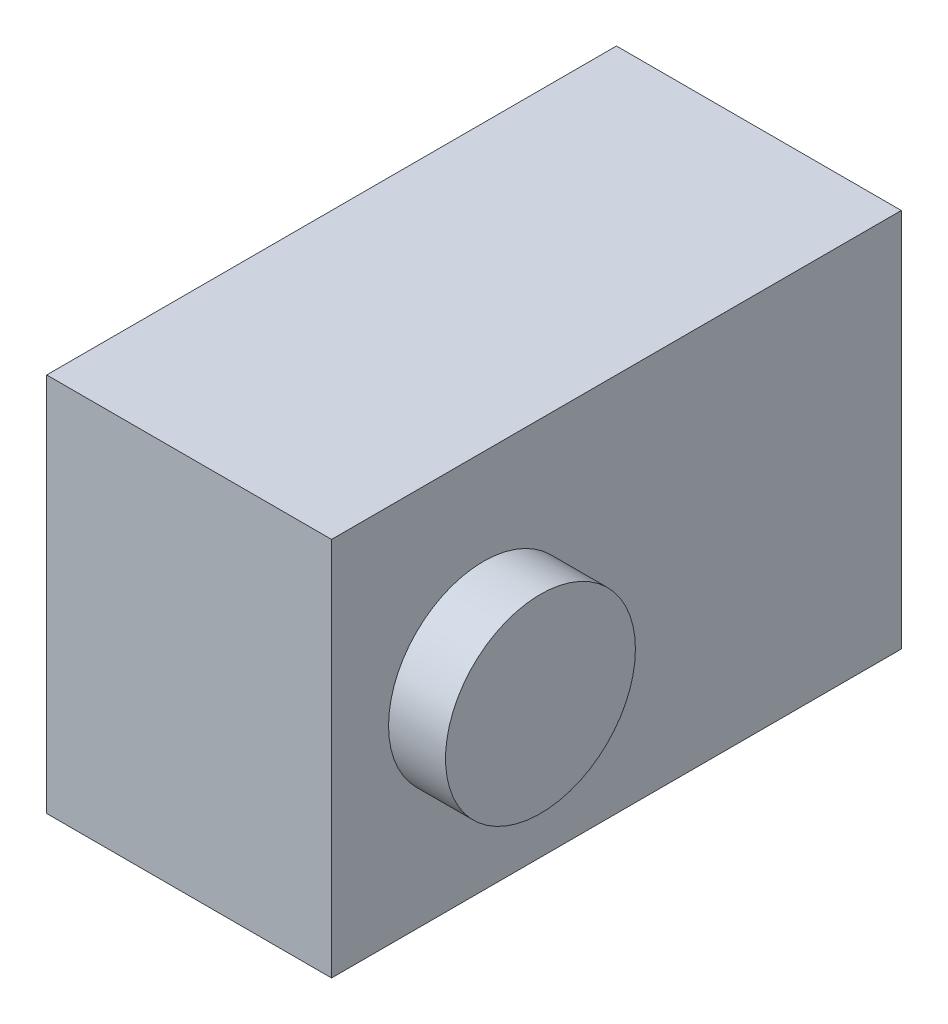
SolidWorks part; units mm, degrees
ref_plane "Ebene vorne" through (0, 0, 0) normal (0, 0, 1) x (1, 0, 0)
ref_plane "Ebene oben" through (0, 0, 0) normal (0, 1, 0) x (1, 0, 0)
ref_plane "Ebene rechts" through (0, 0, 0) normal (1, 0, 0) x (0, 0, -1)
sketch "Skizze1" plane through (0, 0, 0) normal (0, 0, 1) x (1, 0, 0)
  line L1 (0, 0) -> (15, 0)
  line L2 (0, 0) -> (0, 20)
  line L3 (0, 20) -> (15, 20)
  line L4 (15, 0) -> (15, 20)
  dimension "D1" = 15
  dimension "D2" = 20
extrude "Aufsatz-Linear austragen8" add sketch "Skizze1" along normal blind 30
sketch "Skizze2" plane through (15, 0, 0) normal (1, 0, 0) x (0, 0, -1)
  circle A0 centre (-22, 10) radius 5
extrude "Aufsatz-Linear austragen10" add sketch "Skizze2" along normal blind 3 and the other way blind 18 from offset 0
move or copy body "Körper-Verschieben/Kopieren1" bodies to move or copy 112 copy no translate (3, 0, 0) parameters "D1"=3, "D2"=0, "D3"=0
